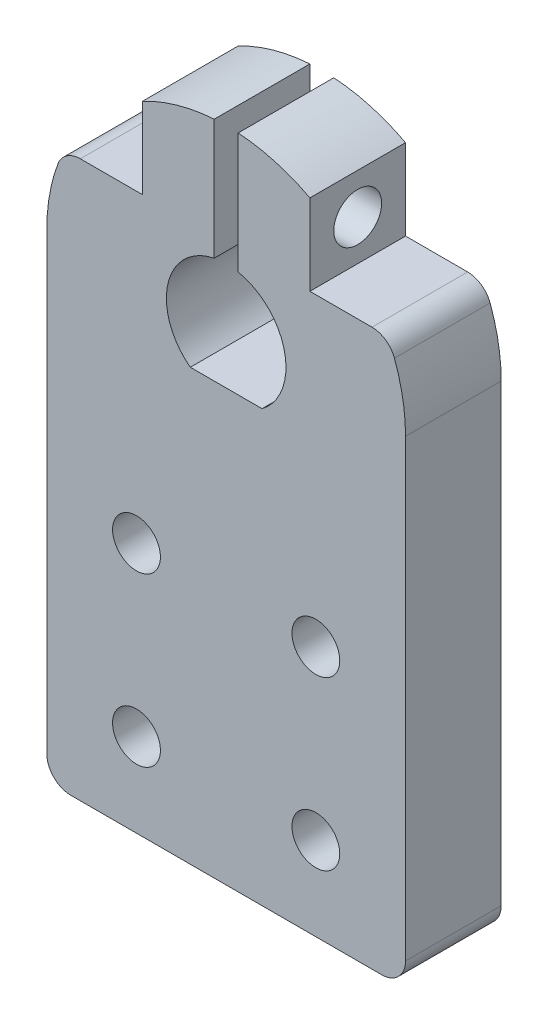
SolidWorks part; units mm, degrees
material "6061 合金"
ref_plane "前视基准面" through (0, 0, 0) normal (0, 0, 1) x (1, 0, 0)
ref_plane "上视基准面" through (0, 0, 0) normal (0, 1, 0) x (1, 0, 0)
ref_plane "右视基准面" through (0, 0, 0) normal (1, 0, 0) x (0, 0, -1)
sketch "草图1" plane through (0, 0, 0) normal (0, 0, 1) x (1, 0, 0)
  line L0 (-15, 0) -> (-15, -25)
  line L1 (-15, -25) -> (-15, -40)
  line L2 (-15, -40) -> (15, -40)
  line L3 (15, -40) -> (15, 0)
  line L5 (0, -55) -> (0, 55) construction
  line L6 (-3, -4) -> (3, -4)
  line L9 (7, 6.5) -> (13.5185, 6.5)
  line L10 (7, 6.5) -> (7, 13.2665)
  line L12 (1, 4.899) -> (1, 14.9666)
  line L13 (-7, 6.5) -> (-13.5185, 6.5)
  line L14 (-7, 6.5) -> (-7, 13.2665)
  line L15 (-1, 4.899) -> (-1, 14.9666)
  arc A0 (-1, 14.9666) -> (-7, 13.2665) centre (0, 0) ccw
  arc A1 (3, -4) -> (1, 4.899) centre (0, 0) ccw
  arc A2 (-1, 4.899) -> (-3, -4) centre (0, 0) ccw
  arc A3 (7, 13.2665) -> (1, 14.9666) centre (0, 0) ccw
  arc A4 (-13.5185, 6.5) -> (-15, 0) centre (0, 0) ccw
  arc A5 (15, 0) -> (13.5185, 6.5) centre (0, 0) ccw
  dimension "D1" = 30
  dimension "D2" = 25
  dimension "D3" = 15
extrude "凸台-拉伸1" add sketch "草图1" along normal blind 8
sketch "草图2" plane through (7, 0, 0) normal (1, 0, 0) x (0, 0, -1)
  circle A0 centre (-4, 9.8832) radius 2
extrude "切除-拉伸1" cut sketch "草图2" against normal blind 15
sketch "草图3" plane through (0, 0, 8) normal (0, 0, 1) x (1, 0, 0)
  line L0 (0, -4.4) -> (0, 4.4) construction
  line L2 (-15, -40) -> (15, -40) construction
  circle A1 centre (7.5, -19) radius 2
  circle A2 centre (7.5, -33) radius 2
  circle A3 centre (-7.5, -33) radius 2
  circle A4 centre (-7.5, -19) radius 2
  dimension "D1" = 7
  dimension "D2" = 14
  dimension "D3" = 7.5
extrude "切除-拉伸2" cut sketch "草图3" against normal blind 15
fillet "圆角1" radius 2 4 edges at (13.5185, 6.5, 4) (-13.5185, 6.5, 4) (-15, -40, 4) (15, -40, 4)
